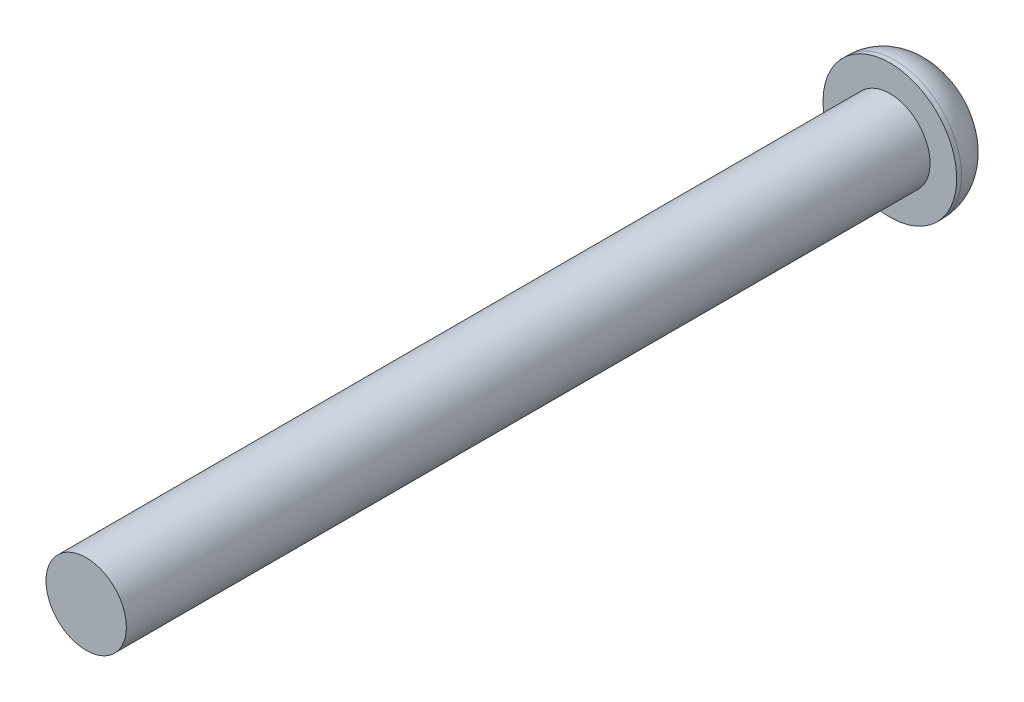
SolidWorks part; units mm, degrees
ref_plane "Front Plane" through (0, 0, 0) normal (0, 0, 1) x (1, 0, 0)
ref_plane "Top Plane" through (0, 0, 0) normal (0, 1, 0) x (1, 0, 0)
ref_plane "Right Plane" through (0, 0, 0) normal (1, 0, 0) x (0, 0, -1)
sketch "Sketch1" plane through (0, 0, 0) normal (0, 0, 1) x (1, 0, 0)
  circle A0 centre (0, 0) radius 2.5
  dimension "D1" = 5
extrude "Boss-Extrude1" add sketch "Sketch1" along normal blind 50
sketch "Sketch2" plane through (0, 0, 0) normal (0, 0, -1) x (-1, 0, 0)
  circle A0 centre (0, 0) radius 4.1596
extrude "Boss-Extrude2" add sketch "Sketch2" along normal blind 2.8
fillet "Fillet1" radius 2.5 1 edges at (-4.1596, 0, -2.8)
sketch "Sketch3" plane through (0, 0, -2.8) normal (0, 0, -1) x (-1, 0, 0)
  line L1 (1.3924, -0.6365) -> (1.2475, 0.8876)
  line L2 (1.2475, 0.8876) -> (-0.145, 1.5241)
  line L3 (-0.145, 1.5241) -> (-1.3924, 0.6365)
  line L4 (-1.3924, 0.6365) -> (-1.2475, -0.8876)
  line L5 (-1.2475, -0.8876) -> (0.145, -1.5241)
  line L6 (0.145, -1.5241) -> (1.3924, -0.6365)
  circle A0 centre (0, 0) radius 1.3259 construction
extrude "Cut-Extrude1" cut sketch "Sketch3" against normal blind 2
